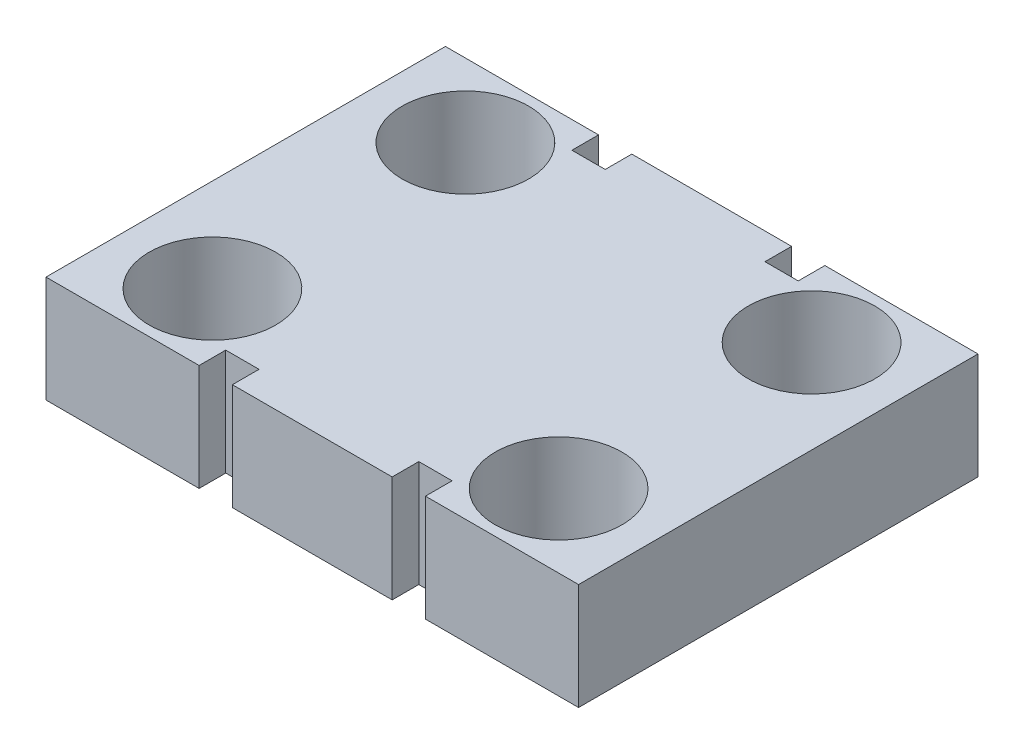
SolidWorks part; units mm, degrees
ref_plane "Płaszczyzna przednia" through (0, 0, 0) normal (0, 0, 1) x (1, 0, 0)
ref_plane "Płaszczyzna górna" through (0, 0, 0) normal (0, 1, 0) x (1, 0, 0)
ref_plane "Płaszczyzna prawa" through (0, 0, 0) normal (1, 0, 0) x (0, 0, -1)
sketch "Sketch1" plane through (0, 0, 0) normal (0, 1, 0) x (1, 0, 0)
  line L1 (-40, 30) -> (0, 30)
  line L2 (-40, 30) -> (-40, 0)
  line L3 (-40, 0) -> (0, 0)
  line L4 (0, 30) -> (0, 0)
  dimension "D1" = 40
  dimension "D2" = 30
extrude "Boss-Extrude1" add sketch "Sketch1" along normal blind 8
sketch "Sketch2" plane through (0, 8, 0) normal (0, 1, 0) x (1, 0, 0)
  line L0 (-40, 15) -> (-9.7076, 15) construction
  line L1 (-20, 30) -> (-20, -8.7627) construction
  line L2 (-40, 30) -> (-40, 0) construction
  line L3 (0, 30) -> (-40, 30) construction
  circle A0 centre (-33, 24.5) radius 4.75
  circle A1 centre (-33, 5.5) radius 4.75
  circle A2 centre (-7, 5.5) radius 4.75
  circle A3 centre (-7, 24.5) radius 4.75
  dimension "D1" = 9.5
  dimension "D2" = 7
  dimension "D3" = 5.5
extrude "Cut-Extrude1" cut sketch "Sketch2" against normal blind 7
sketch "Sketch3" plane through (0, 0, 0) normal (0, -1, 0) x (1, 0, 0)
  line L0 (-40, 0) -> (0, -30) construction
  circle A0 centre (-20, -15) radius 3.15
  point P3 (-20, -15)
  dimension "D1" = 6.3
extrude "Cut-Extrude2" cut sketch "Sketch3" against normal blind 5
sketch "Sketch4" plane through (0, 0, 0) normal (0, -1, 0) x (1, 0, 0)
  line L0 (-20, 0) -> (-20, -30) construction
  line L1 (-40, -15) -> (0, -15) construction
  line L2 (-40, 0) -> (0, 0) construction
  line L3 (0, -30) -> (-40, -30) construction
  line L4 (-40, -30) -> (-40, 0) construction
  line L5 (0, 0) -> (0, -30) construction
  line L6 (-11.5, -2) -> (-14, -2)
  line L7 (-28.5, 0) -> (-26, 0)
  line L8 (-28.5, 0) -> (-28.5, -2)
  line L9 (-28.5, -2) -> (-26, -2)
  line L10 (-26, 0) -> (-26, -2)
  line L11 (-14, 0) -> (-14, -2)
  line L12 (-11.5, 0) -> (-14, 0)
  line L13 (-11.5, 0) -> (-11.5, -2)
  line L14 (-11.5, -30) -> (-11.5, -28)
  line L15 (-11.5, -30) -> (-14, -30)
  line L16 (-14, -30) -> (-14, -28)
  line L17 (-11.5, -28) -> (-14, -28)
  line L18 (-28.5, -28) -> (-26, -28)
  line L19 (-26, -30) -> (-26, -28)
  line L20 (-28.5, -30) -> (-26, -30)
  line L21 (-28.5, -30) -> (-28.5, -28)
  dimension "D1" = 2.5
  dimension "D2" = 2
  dimension "D3" = 6
extrude "Cut-Extrude3" cut sketch "Sketch4" against normal blind 15
